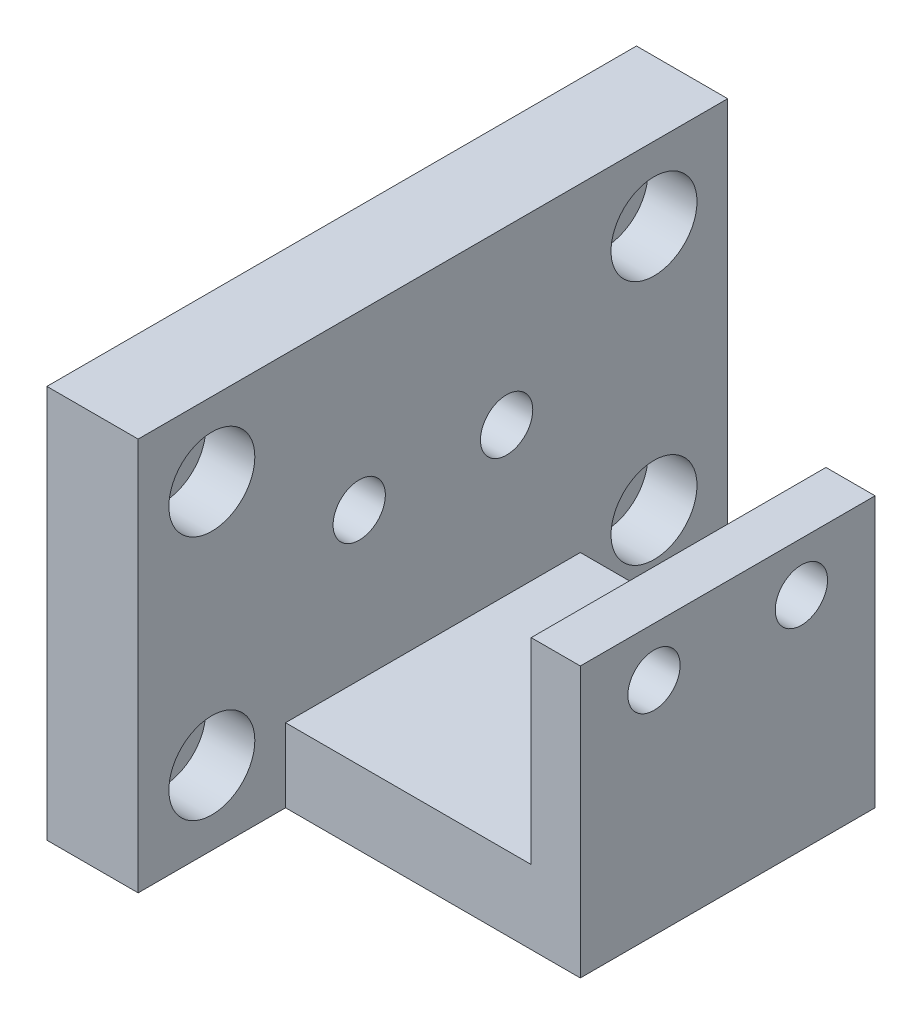
SolidWorks part; units mm, degrees
ref_plane "Front Plane" through (0, 0, 0) normal (0, 0, 1) x (1, 0, 0)
ref_plane "Top Plane" through (0, 0, 0) normal (0, 1, 0) x (1, 0, 0)
ref_plane "Right Plane" through (0, 0, 0) normal (1, 0, 0) x (0, 0, -1)
sketch "Sketch1" plane through (0, 0, 0) normal (1, 0, 0) x (0, 0, -1)
  line L1 (-38.1, -25.4) -> (38.1, -25.4)
  line L2 (-38.1, -25.4) -> (-38.1, 25.4)
  line L3 (-38.1, 25.4) -> (38.1, 25.4)
  line L4 (38.1, -25.4) -> (38.1, 25.4)
  line L5 (-38.1, -25.4) -> (38.1, 25.4) construction
  line L6 (-38.1, 25.4) -> (38.1, -25.4) construction
  point P0 (0, 0)
  dimension "D1" = 76.2
  dimension "D2" = 50.8
extrude "Boss-Extrude1" add sketch "Sketch1" along normal blind 11.7927
sketch "Sketch7" plane through (0, 0, 38.1) normal (0, 0, 1) x (1, 0, 0)
  line L0 (11.7927, -25.4) -> (49.8927, -25.4)
  line L1 (49.8927, -25.4) -> (49.8927, 9.525)
  line L2 (49.8927, 9.525) -> (43.5427, 9.525)
  line L3 (43.5427, 9.525) -> (43.5427, -15.875)
  line L4 (43.5427, -15.875) -> (11.7927, -15.875)
  line L6 (11.7927, -15.875) -> (11.7927, -25.4)
  line L7 (11.7927, -25.4) -> (0, -25.4) construction
  line L8 (11.7927, 25.4) -> (11.7927, -25.4) construction
  point P3 (11.7927, -25.4)
  dimension "D1" = 25.4
  dimension "D2" = 9.525
  dimension "D3" = 6.35
  dimension "D4" = 31.75
extrude "Boss-Extrude2" add sketch "Sketch7" against normal mid plane 38.1 from offset 38.1 offset against normal yes
hole_wizard "1/4 Clearance Hole2" positions "Sketch28" profile "Sketch29" hole size "1/4" standard "ANSI Inch" end condition through all
sketch "Sketch28" plane through (49.8927, 0, 0) normal (1, 0, 0) x (0, 0, -1)
  line L0 (19.05, -15.875) -> (-19.05, -15.875) construction
  line L1 (-19.05, -25.4) -> (-19.05, 9.525) construction
  point P0 (-9.525, 3.175)
  point P2 (9.525, 3.175)
  dimension "D1" = 19.05
  dimension "D2" = 19.05
  dimension "D3" = 9.525
sketch "Sketch29" plane through (49.8927, 3.175, 9.525) normal (0, 1, 0) x (0, 0, -1)
  line L0 (0, 0) -> (0, 49.8927)
  line L1 (0, 49.8927) -> (3.3782, 49.8927)
  line L2 (3.3782, 49.8927) -> (3.3782, 0)
  line L5 (3.3782, 0) -> (0, 0)
  line L11 (0, -6.35) -> (0, 107.95) construction
  dimension "Thru Hole Dia." = 6.7564
  dimension "Thru Hole Depth" = 49.8927
hole_wizard "CBORE for 1/4 Socket Head Cap Screw1" positions "Sketch32" profile "Sketch33" counterbore size "1/4" standard "ANSI Inch" end condition through all
sketch "Sketch32" plane through (11.7927, 0, 0) normal (1, 0, 0) x (0, 0, -1)
  line L0 (-38.1, -25.4) -> (-19.05, -25.4) construction
  line L2 (38.1, 25.4) -> (-38.1, 25.4) construction
  line L3 (38.1, -25.4) -> (38.1, 25.4) construction
  line L4 (-38.1, 25.4) -> (-38.1, -25.4) construction
  point P0 (-28.575, 15.875)
  point P2 (28.575, 15.875)
  point P4 (28.575, -15.875)
  point P6 (-28.575, -15.875)
  point P13 (0, 0)
  point P14 (0, 0)
  point P15 (0, 0)
  point P16 (0, 0)
  point P17 (0, 0)
  point P18 (0, 0)
  point P19 (0, 0)
  point P20 (0, 0)
  dimension "D1" = 9.525
  dimension "D2" = 9.525
  dimension "D3" = 9.525
  dimension "D4" = 9.525
sketch "Sketch33" plane through (11.7927, 15.875, 28.575) normal (0, 1, 0) x (0, 0, -1)
  line L0 (0, 0) -> (0, 11.7927)
  line L1 (0, 11.7927) -> (3.3782, 11.7927)
  line L3 (3.3782, 11.7927) -> (3.3782, 6.35)
  line L4 (3.3782, 6.35) -> (5.5562, 6.35)
  line L5 (5.5562, 6.35) -> (5.5562, 0)
  line L7 (5.5562, 0) -> (0, 0)
  line L11 (0, -6.35) -> (0, 107.95) construction
  dimension "Thru Hole Dia." = 6.7564
  dimension "Thru Hole Depth" = 11.7927
  dimension "C'Bore Dia." = 11.1125
  dimension "C'Bore Depth" = 6.35
